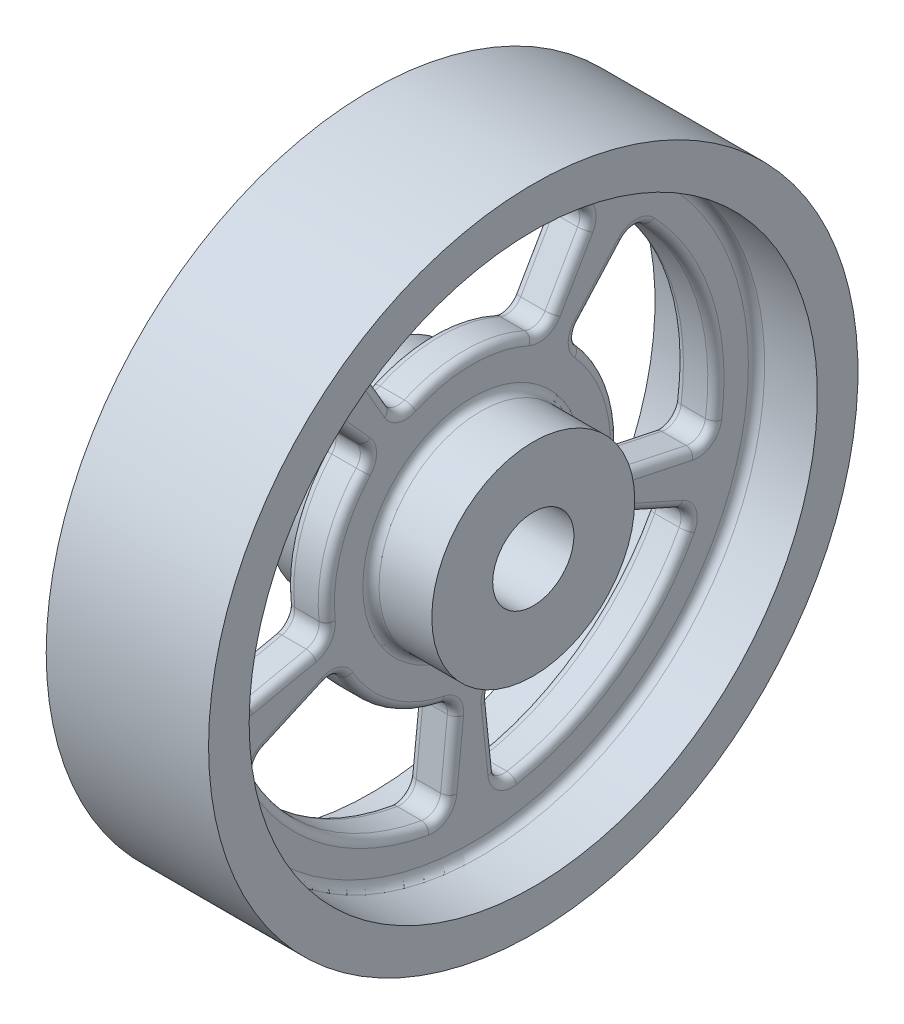
SolidWorks part; units mm, degrees
ref_plane "Front Plane" through (0, 0, 0) normal (0, 0, 1) x (1, 0, 0)
ref_plane "Top Plane" through (0, 0, 0) normal (0, 1, 0) x (1, 0, 0)
ref_plane "Right Plane" through (0, 0, 0) normal (1, 0, 0) x (0, 0, -1)
sketch "Sketch2" plane through (0, 0, 0) normal (0, 0, 1) x (1, 0, 0)
  line L0 (0, 0) -> (0, 41.5136) construction
  line L1 (0, 0) -> (61.0797, 0) construction
  line L2 (-10, 35) -> (-2.5, 35)
  line L3 (10, 5) -> (-10, 5)
  line L4 (10, 5) -> (10, 12.5)
  line L5 (10, 12.5) -> (2.5, 12.5)
  line L6 (-10, 5) -> (-10, 12.5)
  line L7 (10, 5) -> (-10, 12.5) construction
  line L8 (10, 12.5) -> (-10, 5) construction
  line L10 (2.5, 35) -> (2.5, 12.5)
  line L12 (-2.5, 35) -> (-2.5, 12.5)
  line L13 (2.5, 35) -> (-2.5, 12.5) construction
  line L14 (2.5, 12.5) -> (-2.5, 35) construction
  line L15 (10, 40) -> (-10, 40)
  line L16 (10, 40) -> (10, 35)
  line L17 (10, 35) -> (2.5, 35)
  line L18 (-10, 40) -> (-10, 35)
  line L19 (10, 40) -> (-10, 35) construction
  line L20 (10, 35) -> (-10, 40) construction
  line L21 (-10, 12.5) -> (-2.5, 12.5)
  line L23 (-10, 35) -> (-10, 12.5) construction
  line L24 (10, 35) -> (10, 12.5) construction
  point P3 (0, 8.75)
  point P9 (0, 23.75)
  point P14 (0, 37.5)
  dimension "D1" = 5
  dimension "D3" = 5
  dimension "D4" = 10
  dimension "D5" = 25
  dimension "D6" = 80
  dimension "D7" = 20
revolve "Revolve1" add sketch "Sketch2" angle 360 mid plane about L1
sketch "Sketch4" plane through (2.5, 0, 0) normal (1, 0, 0) x (0, 0, -1)
  line L0 (-15, 25.9808) -> (-9, 15.5885)
  line L1 (9, 15.5885) -> (15, 25.9808)
  line L2 (0, 0) -> (0, 47.8452) construction
  arc A0 (15, 25.9808) -> (-15, 25.9808) centre (0, 0) ccw
  arc A1 (-9, 15.5885) -> (9, 15.5885) centre (0, 0) cw
  dimension "D1" = 18
  dimension "D2" = 30
  dimension "D3" = 60
extrude "Cut-Extrude1" cut sketch "Sketch4" against normal through all
fillet "Fillet2" radius 2 1 edges at (0, 25.9808, -15)
fillet "Fillet3" radius 2 1 edges at (0, 15.5885, -9)
fillet "Fillet4" radius 2 1 edges at (0, 15.5885, 9)
fillet "Fillet5" radius 2 1 edges at (0, 25.9808, 15)
pattern_circular "CirPattern1" count 5 over 360 about axis through (0, 0, 0) along (1, 0, 0) of "Cut-Extrude1", "Fillet2", "Fillet3", "Fillet4", "Fillet5"
fillet "Fillet11" radius 1 42 edges at (2.5, 0, 12.5) (2.5, 0, 35) (2.5, 16.3302, 8.8315) (2.5, 18, 0) (2.5, 16.3302, -8.8315) (2.5, 20.7102, -11.9571) (2.5, 25.7731, -14.1443) (2.5, 30, 0) (2.5, 25.7731, 14.1443) (2.5, 20.7102, 11.9571) (2.5, 13.4456, -12.8018) (2.5, 5.5623, -17.119) (2.5, -3.353, -18.26) (2.5, -4.972, -23.3915) (2.5, -5.4877, -28.8825) (2.5, 9.2705, -28.5317) (2.5, 21.4164, -20.1409) (2.5, 17.7717, -16.0017) (2.5, -8.0203, -16.7435) (2.5, -14.5623, -10.5801) (2.5, -18.4024, -2.4538) (2.5, -23.7831, -2.4997) (2.5, -29.1647, -3.7061) (2.5, -24.2705, -17.6336) (2.5, -12.5371, -26.592) (2.5, -9.7267, -21.8466) (2.5, -18.4024, 2.4538) (2.5, -14.5623, 10.5801) (2.5, -8.0203, 16.7435) (2.5, -9.7267, 21.8466) (2.5, -12.5371, 26.592) (2.5, -24.2705, 17.6336) (2.5, -29.1647, 3.7061) (2.5, -23.7831, 2.4997) (2.5, -3.353, 18.26) (2.5, 5.5623, 17.119) (2.5, 13.4456, 12.8018) (2.5, 17.7717, 16.0017) (2.5, 21.4164, 20.1409) (2.5, 9.2705, 28.5317) (2.5, -5.4877, 28.8825) (2.5, -4.972, 23.3915)
fillet "Fillet12" radius 1 42 edges at (-2.5, 0, 35) (-2.5, 0, 12.5) (-2.5, 25.7731, -14.1443) (-2.5, 20.7102, -11.9571) (-2.5, 16.3302, -8.8315) (-2.5, 18, 0) (-2.5, 16.3302, 8.8315) (-2.5, 20.7102, 11.9571) (-2.5, 25.7731, 14.1443) (-2.5, 30, 0) (-2.5, -5.4877, -28.8825) (-2.5, -4.972, -23.3915) (-2.5, -3.353, -18.26) (-2.5, 5.5623, -17.119) (-2.5, 13.4456, -12.8018) (-2.5, 17.7717, -16.0017) (-2.5, 21.4164, -20.1409) (-2.5, 9.2705, -28.5317) (-2.5, -29.1647, -3.7061) (-2.5, -23.7831, -2.4997) (-2.5, -18.4024, -2.4538) (-2.5, -14.5623, -10.5801) (-2.5, -8.0203, -16.7435) (-2.5, -9.7267, -21.8466) (-2.5, -12.5371, -26.592) (-2.5, -24.2705, -17.6336) (-2.5, -12.5371, 26.592) (-2.5, -9.7267, 21.8466) (-2.5, -8.0203, 16.7435) (-2.5, -14.5623, 10.5801) (-2.5, -18.4024, 2.4538) (-2.5, -23.7831, 2.4997) (-2.5, -29.1647, 3.7061) (-2.5, -24.2705, 17.6336) (-2.5, 21.4164, 20.1409) (-2.5, 17.7717, 16.0017) (-2.5, 13.4456, 12.8018) (-2.5, 5.5623, 17.119) (-2.5, -3.353, 18.26) (-2.5, -4.972, 23.3915) (-2.5, -5.4877, 28.8825) (-2.5, 9.2705, 28.5317)
